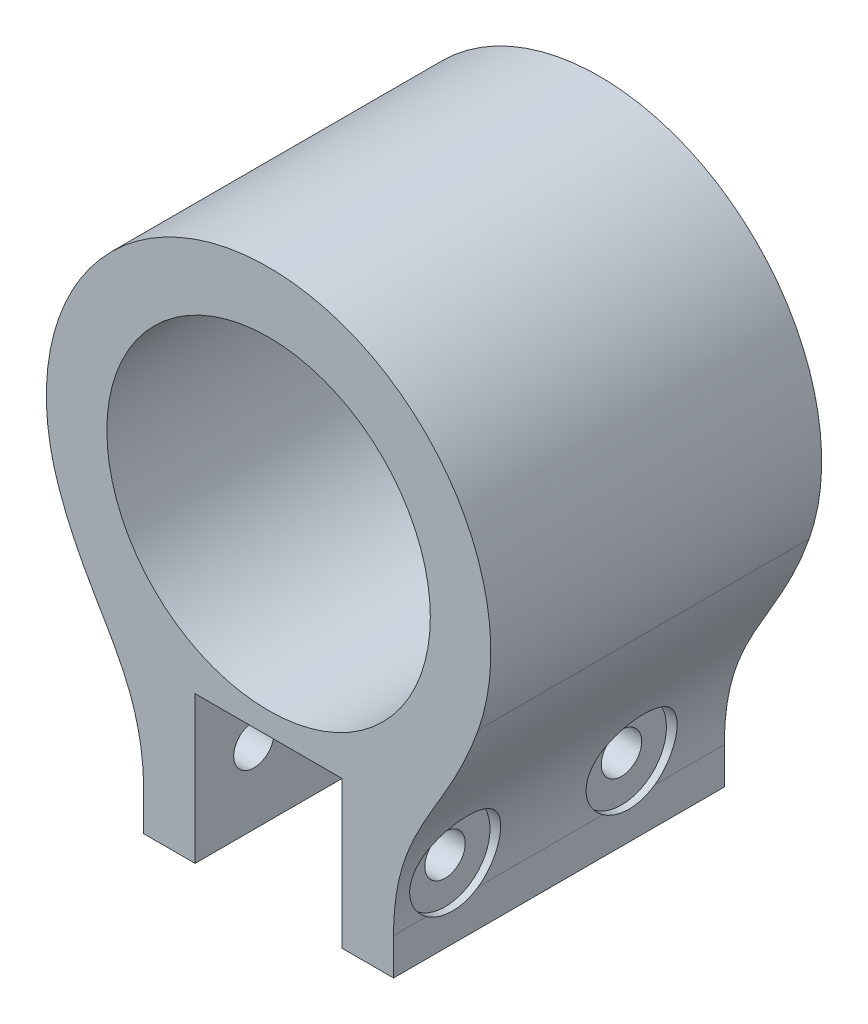
SolidWorks part; units mm, degrees
ref_plane "Front Plane" through (0, 0, 0) normal (0, 0, 1) x (1, 0, 0)
ref_plane "Top Plane" through (0, 0, 0) normal (0, 1, 0) x (1, 0, 0)
ref_plane "Right Plane" through (0, 0, 0) normal (1, 0, 0) x (0, 0, -1)
sketch "Sketch1" plane through (0, 0, 0) normal (0, 0, 1) x (1, 0, 0)
  line L0 (0, -10) -> (0, 35) construction
  line L1 (-10, -10) -> (10, -10)
  line L2 (-10, -10) -> (-10, 10)
  line L3 (-10, 10) -> (10, 10)
  line L4 (10, -10) -> (10, 10)
  line L5 (-10, -10) -> (10, 10) construction
  line L6 (-10, 10) -> (10, -10) construction
  line L7 (-10, -10) -> (-17, -10)
  line L8 (-10, -10) -> (-10, 10)
  line L9 (-10, 10) -> (-17, 10)
  line L10 (-17, -10) -> (-17, 10)
  line L11 (10, -10) -> (17, -10)
  line L12 (10, -10) -> (10, 10)
  line L13 (10, 10) -> (17, 10)
  line L14 (17, -10) -> (17, 10)
  circle A0 centre (0, 35) radius 22
  circle A1 centre (0, 35) radius 30.2324
  spline S0 degree 3 poles (-28.5307, 25) (-24.1369, 12.4643) (-17, 8.6194) (-17, -5) knots 0 0 0 0 1 1 1 1
  spline S1 degree 3 poles (28.5307, 25) (24.1369, 12.4643) (17, 8.6194) (17, -5) knots 0 0 0 0 1 1 1 1
  point P2 (0, 0)
  dimension "D1" = 44
  dimension "D2" = 20
  dimension "D3" = 20
  dimension "D4" = 7
  dimension "D5" = 7
  dimension "D6" = 25
  dimension "D7" = 5
  dimension "D8" = 15
extrude "Boss-Extrude1" add sketch "Sketch1" along normal blind 40 contours L13 A1 L9 L3 A0 | A1 S0 L10 | A1 L10 L7 L2 | A1 L4 L11 L14 | S1 A1 L14 | L9 A1 L8 | L12 A1 L13
hole_wizard "CBORE for M5 Hex Head Bolt1" positions "Sketch2" profile "Sketch4" counterbore size "M5" standard "ANSI Metric"
sketch "Sketch2" plane through (-17, 0, 0) normal (-1, 0, 0) x (0, 0, 1)
  line L0 (40, -10) -> (0, -10) construction
  line L1 (0, -10) -> (0, -5) construction
  line L2 (40, -10) -> (40, -5) construction
  point P0 (8, 0)
  point P2 (32, 0)
  dimension "D1" = 10
  dimension "D2" = 8
  dimension "D3" = 8
sketch "Sketch4" plane through (-17, 0, 8) normal (0, 1, 0) x (0, 0, 1)
  line L0 (0, 0) -> (0, 13.6524)
  line L1 (0, 13.6524) -> (2.75, 12)
  line L2 (2.75, 12) -> (2.75, 1)
  line L3 (2.75, 1) -> (6.12, 1)
  line L4 (6.12, 1) -> (6.12, 0)
  line L5 (6.12, 0) -> (0, 0)
  line L10 (0, 13.6524) -> (-2.75, 12) construction
  line L11 (0, -6.35) -> (0, 107.95) construction
  dimension "Hole Dia." = 5.5
  dimension "Hole Depth" = 12
  dimension "C'Bore Dia." = 12.24
  dimension "C'Bore Depth" = 1
  dimension "Drill Angle" = 118
sketch "Sketch5" plane through (-17, 0, 0) normal (-1, 0, 0) x (0, 0, 1)
  arc A0 (4.4709, -5) -> (11.5291, -5) centre (8, 0) ccw construction
  arc A1 (4.4709, -5) -> (11.5291, -5) centre (8, 0) ccw
  arc A2 (28.4709, -5) -> (35.5291, -5) centre (32, 0) ccw construction
  arc A3 (28.4709, -5) -> (35.5291, -5) centre (32, 0) ccw
  circle A4 centre (8, 0) radius 6.12
  circle A5 centre (32, 0) radius 6.12
  arc M1 (11.5291, -5) -> (4.4709, -5) centre (8, 0) cw
  arc M7 (35.5291, -5) -> (28.4709, -5) centre (32, 0) cw
extrude "Cut-Extrude1" cut sketch "Sketch5" along normal through all contours A4 M1 | A5 M7
mirror "Mirror1" about plane through (0, 0, 0) normal (1, 0, 0) of "Cut-Extrude1", "CBORE for M5 Hex Head Bolt1"
sketch "Sketch6" plane through (0, 0, 0) normal (0, 0, -1) x (-1, 0, 0)
  line L0 (17, -10) -> (17, -5) construction
  line L1 (-17, -10) -> (-17, -5) construction
  line L2 (17, -10) -> (17, -5)
  line L3 (-17, -10) -> (-17, -5)
  line L4 (-17, -10) -> (17, -10)
  arc A0 (28.5307, 25) -> (-28.5307, 25) centre (0, 35) ccw construction
  arc A1 (28.5307, 25) -> (-28.5307, 25) centre (0, 35) ccw
  circle A2 centre (0, 35) radius 9
  spline S0 degree 3 poles (-1156.8577, 2778.0678) (1385.5719, -2540.4398) (-1423.9063, 2527.0429) (1448.5426, -2640.9941) knots -4.754699 -4.754699 -4.754699 -4.754699 5.620306 5.620306 5.620306 5.620306 only from (28.5307, 25) to (17, -5) construction
  spline S1 degree 3 poles (1156.8577, 2778.0678) (-1385.5719, -2540.4398) (1423.9063, 2527.0429) (-1448.5426, -2640.9941) knots -4.754699 -4.754699 -4.754699 -4.754699 5.620306 5.620306 5.620306 5.620306 only from (-28.5307, 25) to (-17, -5) construction
  spline S2 degree 3 poles (28.5307, 25) (24.1369, 12.4643) (17, 8.6194) (17, -5) knots 0 0 0 0 1 1 1 1
  spline S3 degree 3 poles (-28.5307, 25) (-24.1369, 12.4643) (-17, 8.6194) (-17, -5) knots 0 0 0 0 1 1 1 1
  dimension "D1" = 18
extrude "Boss-Extrude2" add sketch "Sketch6" along normal blind 5
hole_wizard "M5 Clearance Hole1" positions "Sketch7" profile "Sketch8" hole size "M5" standard "ANSI Metric"
sketch "Sketch7" plane through (0, 0, 0) normal (0, 0, 1) x (1, 0, 0)
  point P0 (0, 0)
sketch "Sketch8" plane through (0, 0, 0) normal (1, 0, 0) x (0, -1, 0)
  line L0 (0, 0) -> (0, 13.6524)
  line L1 (0, 13.6524) -> (2.75, 12)
  line L2 (2.75, 12) -> (2.75, 0)
  line L5 (2.75, 0) -> (0, 0)
  line L10 (0, 13.6524) -> (-2.75, 12) construction
  line L11 (0, -6.35) -> (0, 107.95) construction
  dimension "Hole Dia." = 5.5
  dimension "Hole Depth" = 12
  dimension "Drill Angle" = 118
hole_wizard "M4 Clearance Hole1" positions "Sketch9" profile "Sketch10" hole size "M4" standard "ANSI Metric"
sketch "Sketch9" plane through (0, 0, -5) normal (0, 0, -1) x (-1, 0, 0)
  line L1 (-14.5, 35) -> (14.5, 35) construction
  circle A0 centre (0, 35) radius 9 construction
  circle A1 centre (0, 35) radius 9
  point P0 (-14.5, 35)
  point P2 (14.5, 35)
  point P37 (0, 35)
  dimension "D1" = 29
sketch "Sketch10" plane through (14.5, 35, -5) normal (1, 0, 0) x (0, 1, 0)
  line L0 (0, 0) -> (0, 13.3519)
  line L1 (0, 13.3519) -> (2.25, 12)
  line L2 (2.25, 12) -> (2.25, 0)
  line L5 (2.25, 0) -> (0, 0)
  line L10 (0, 13.3519) -> (-2.25, 12) construction
  line L11 (0, -6.35) -> (0, 107.95) construction
  dimension "Hole Dia." = 4.5
  dimension "Hole Depth" = 12
  dimension "Drill Angle" = 118
sketch "Sketch11" plane through (0, 0, -5) normal (0, 0, -1) x (-1, 0, 0)
  arc A2 (-12.145, 42.9214) -> (-7.9214, 47.145) centre (0, 35) cw construction
  arc A3 (-9.2872, 49.239) -> (-14.239, 44.2872) centre (0, 35) ccw
  arc A4 (-6.5556, 45.051) -> (-10.051, 41.5556) centre (0, 35) ccw
  arc A5 (-6.5556, 45.051) -> (-9.2872, 49.239) centre (-7.9214, 47.145) ccw
  arc A6 (-14.239, 44.2872) -> (-10.051, 41.5556) centre (-12.145, 42.9214) ccw
  circle A7 centre (-14.5, 35) radius 2.25 construction
  circle A8 centre (-14.5, 35) radius 2.25
  arc A9 (10.051, 41.5556) -> (6.5556, 45.051) centre (0, 35) ccw
  arc A10 (10.051, 41.5556) -> (14.239, 44.2872) centre (12.145, 42.9214) ccw
  arc A11 (9.2872, 49.239) -> (6.5556, 45.051) centre (7.9214, 47.145) ccw
  arc A12 (14.239, 44.2872) -> (9.2872, 49.239) centre (0, 35) ccw
  arc A13 (7.9214, 47.145) -> (12.145, 42.9214) centre (0, 35) cw construction
  arc A14 (6.5556, 24.949) -> (10.051, 28.4444) centre (0, 35) ccw
  arc A15 (6.5556, 24.949) -> (9.2872, 20.761) centre (7.9214, 22.855) ccw
  arc A16 (14.239, 25.7128) -> (10.051, 28.4444) centre (12.145, 27.0786) ccw
  arc A17 (9.2872, 20.761) -> (14.239, 25.7128) centre (0, 35) ccw
  arc A18 (12.145, 27.0786) -> (7.9214, 22.855) centre (0, 35) cw construction
  arc A19 (-10.051, 28.4444) -> (-6.5556, 24.949) centre (0, 35) ccw
  arc A20 (-10.051, 28.4444) -> (-14.239, 25.7128) centre (-12.145, 27.0786) ccw
  arc A21 (-9.2872, 20.761) -> (-6.5556, 24.949) centre (-7.9214, 22.855) ccw
  arc A22 (-14.239, 25.7128) -> (-9.2872, 20.761) centre (0, 35) ccw
  arc A23 (-7.9214, 22.855) -> (-12.145, 27.0786) centre (0, 35) cw construction
  point P6 (-10.253, 45.253)
  point P17 (10.253, 45.253)
  point P24 (10.253, 24.747)
  point P31 (-10.253, 24.747)
  dimension "D1" = 2.5
  dimension "D2" = 4
extrude "Cut-Extrude2" cut sketch "Sketch11" against normal up to next
